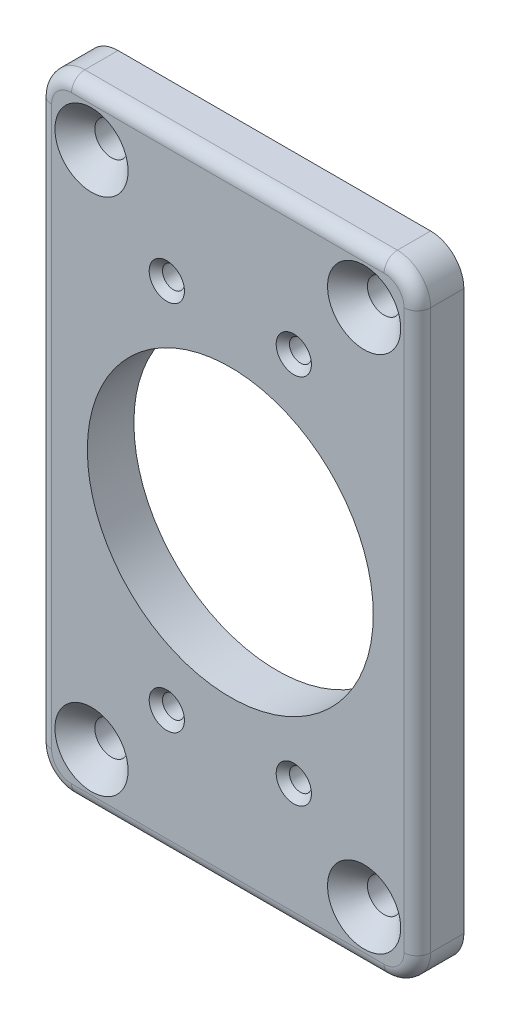
SolidWorks part; units mm, degrees
ref_plane "Front Plane" through (0, 0, 0) normal (0, 0, 1) x (1, 0, 0)
ref_plane "Top Plane" through (0, 0, 0) normal (0, 1, 0) x (1, 0, 0)
ref_plane "Right Plane" through (0, 0, 0) normal (1, 0, 0) x (0, 0, -1)
sketch "Sketch1" plane through (0, 0, 0) normal (0, 0, 1) x (1, 0, 0)
  line L0 (-27.675, -9.35) -> (-8.575, -9.35)
  line L1 (-47, 10) -> (10, 10)
  line L2 (-47, 10) -> (-47, -84)
  line L3 (-47, -84) -> (10, -84)
  line L4 (10, 10) -> (10, -84)
  line L5 (-47, 10) -> (10, -84) construction
  line L6 (-47, -84) -> (10, 10) construction
  line L7 (-31, -5.925) -> (-6, -5.925)
  line L8 (-31, -5.925) -> (-31, -68.075)
  line L9 (-31, -68.075) -> (-6, -68.075)
  line L10 (-6, -5.925) -> (-6, -68.075)
  line L11 (-31, -5.925) -> (-6, -68.075) construction
  line L12 (-31, -68.075) -> (-6, -5.925) construction
  line L13 (-31, -5.925) -> (-27.675, -5.925)
  line L14 (-31, -5.925) -> (-31, -9.35)
  line L15 (-31, -9.35) -> (-27.675, -9.35)
  line L16 (-27.675, -5.925) -> (-27.675, -9.35)
  line L17 (-31, -5.925) -> (-27.675, -9.35) construction
  line L18 (-31, -9.35) -> (-27.675, -5.925) construction
  line L19 (-27.675, -9.35) -> (-27.675, -65.25)
  line L20 (-27.675, -65.25) -> (-8.575, -65.25)
  line L21 (-18.5, -37) -> (-13.1397, -37)
  line L22 (-47, 10) -> (-31, 10)
  line L23 (-47, 10) -> (-47, -5.925)
  line L24 (-47, -5.925) -> (-31, -5.925)
  line L25 (-31, 10) -> (-31, -5.925)
  line L26 (-47, 10) -> (-31, -5.925) construction
  line L27 (-47, -5.925) -> (-31, 10) construction
  line L28 (-13.1397, -37) -> (-18.5, -37)
  line L29 (-18.5, -37) -> (-18.5, -29.994)
  circle A2 centre (-27.675, -9.35) radius 1.65
  circle A3 centre (-8.575, -9.35) radius 1.65
  circle A4 centre (-27.675, -65.25) radius 1.65
  circle A5 centre (-8.575, -65.25) radius 1.65
  circle A6 centre (-39, 2.0375) radius 2.5
  circle A7 centre (-39, -76.0375) radius 2.5
  circle A8 centre (2, 2.0375) radius 2.5
  circle A9 centre (2, -76.0375) radius 2.5
  point P0 (-18.5, -37)
  point P13 (-29.3375, -7.6375)
  point P24 (-39, 2.0375)
  dimension "D1" = 62.15
  dimension "D2" = 25
  dimension "D9" = 3.3
  dimension "D10" = 3.3
  dimension "D11" = 3.3
  dimension "D12" = 3.3
  dimension "D13" = 5
  dimension "D3" = 94
  dimension "D4" = 57
  dimension "D5" = 3.325
  dimension "D6" = 3.425
  dimension "D7" = 19.1
  dimension "D8" = 55.9
extrude "Boss-Extrude1" add sketch "Sketch1" along normal blind 7
chamfer "Chamfer1" distance 3 angle 45 4 edges at (4.5, 2.0375, 7) (-36.5, 2.0375, 7) (-36.5, -76.0375, 7) (4.5, -76.0375, 7)
fillet "Fillet1" radius 5 4 edges at (10, 10, 3.5) (-47, 10, 3.5) (-47, -84, 3.5) (10, -84, 3.5)
fillet "Fillet2" radius 2 8 edges at (8.5355, -82.5355, 7) (10, -37, 7) (8.5355, 8.5355, 7) (-18.5, 10, 7) (-45.5355, 8.5355, 7) (-47, -37, 7) (-45.5355, -82.5355, 7) (-18.5, -84, 7)
chamfer "Chamfer2" distance 1 angle 45 4 edges at (-6.925, -65.25, 7) (-26.025, -65.25, 7) (-6.925, -9.35, 7) (-26.025, -9.35, 7)
sketch "Sketch3" plane through (0, 0, 7) normal (0, 0, 1) x (1, 0, 0)
  line L1 (-27.675, -9.35) -> (-8.575, -9.35)
  line L2 (-27.675, -9.35) -> (-27.675, -65.25)
  line L3 (-27.675, -65.25) -> (-8.575, -65.25)
  line L4 (-8.575, -9.35) -> (-8.575, -65.25)
  line L5 (-27.675, -9.35) -> (-8.575, -65.25) construction
  line L6 (-27.675, -65.25) -> (-8.575, -9.35) construction
  circle A0 centre (-18.125, -37.3) radius 21.5
  point P4 (-18.125, -37.3)
  dimension "D1" = 43
extrude "Cut-Extrude1" cut sketch "Sketch3" against normal blind 10 contours L2 A0 | L4 A0 L2 | L4 A0
